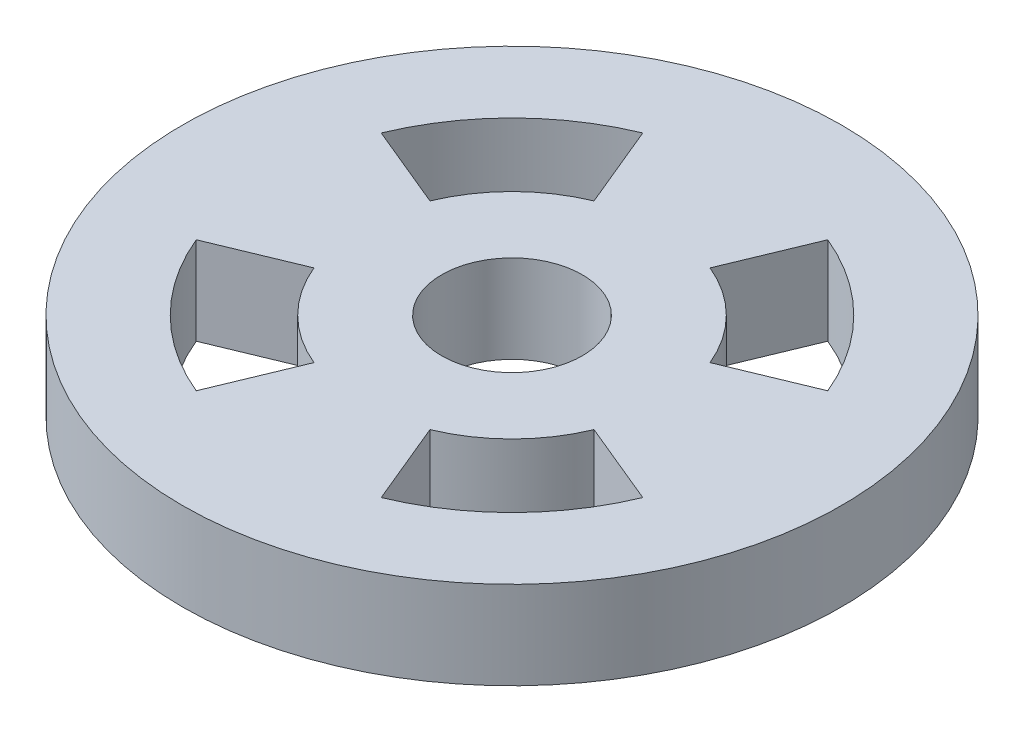
SolidWorks part; units mm, degrees
ref_plane "Front Plane" through (0, 0, 0) normal (0, 0, 1) x (1, 0, 0)
ref_plane "Top Plane" through (0, 0, 0) normal (0, 1, 0) x (1, 0, 0)
ref_plane "Right Plane" through (0, 0, 0) normal (1, 0, 0) x (0, 0, -1)
sketch "Sketch1" plane through (0, 0, 0) normal (0, 1, 0) x (1, 0, 0)
  line L0 (-1.3199, 3.1865) -> (-2.1048, 5.0813)
  line L1 (1.3199, 3.1865) -> (2.1048, 5.0813)
  line L2 (3.1865, 1.3199) -> (5.0813, 2.1048)
  line L3 (3.1865, -1.3199) -> (5.0813, -2.1048)
  line L4 (1.3199, -3.1865) -> (2.1048, -5.0813)
  line L5 (-1.3199, -3.1865) -> (-2.1048, -5.0813)
  line L6 (-3.1865, -1.3199) -> (-5.0813, -2.1048)
  line L7 (-3.1865, 1.3199) -> (-5.0813, 2.1048)
  circle A0 centre (0, 0) radius 7.5
  circle A1 centre (0, 0) radius 1.6
  arc A2 (-1.3199, 3.1865) -> (-3.1865, 1.3199) centre (0, 0) ccw
  arc A3 (-2.1048, 5.0813) -> (-5.0813, 2.1048) centre (0, 0) ccw
  arc A4 (-5.0813, -2.1048) -> (-2.1048, -5.0813) centre (0, 0) ccw
  arc A5 (-3.1865, -1.3199) -> (-1.3199, -3.1865) centre (0, 0) ccw
  arc A6 (1.3199, -3.1865) -> (3.1865, -1.3199) centre (0, 0) ccw
  arc A7 (2.1048, -5.0813) -> (5.0813, -2.1048) centre (0, 0) ccw
  arc A8 (3.1865, 1.3199) -> (1.3199, 3.1865) centre (0, 0) ccw
  arc A9 (5.0813, 2.1048) -> (2.1048, 5.0813) centre (0, 0) ccw
  point P25 (0, 0)
  dimension "D1" = 15
  dimension "D2" = 3.2
  dimension "D3" = 1.8491
  dimension "D4" = 2
  dimension "D5" = 45
  dimension "D6" = 4
extrude "Boss-Extrude1" add sketch "Sketch1" along normal blind 2
